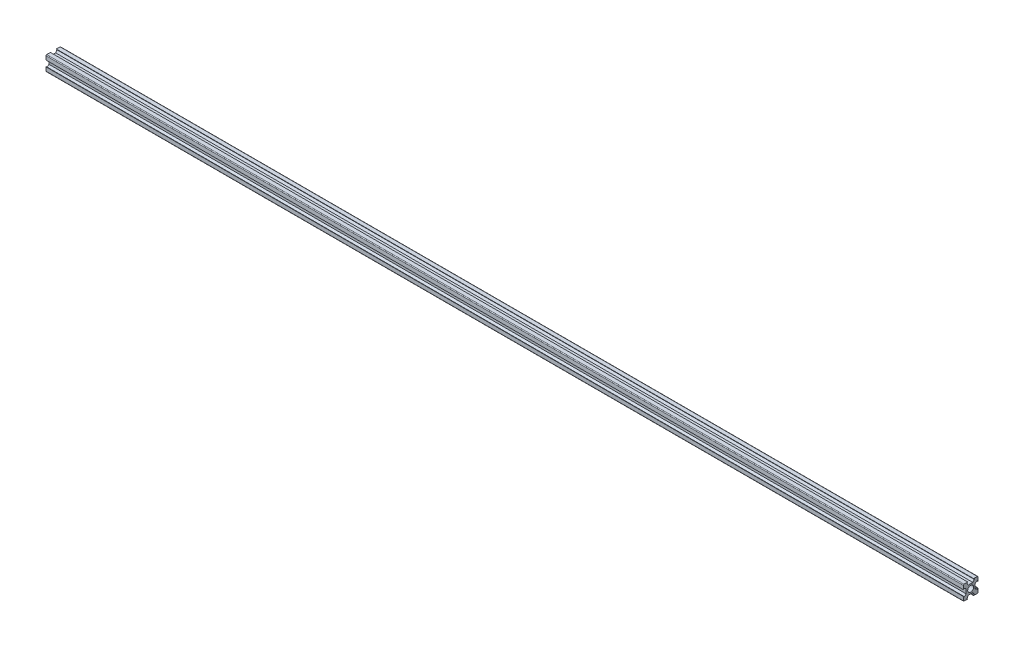
SolidWorks part; units mm, degrees
ref_plane "前视基准面" through (0, 0, 0) normal (0, 0, 1) x (1, 0, 0)
ref_plane "上视基准面" through (0, 0, 0) normal (0, 1, 0) x (1, 0, 0)
ref_plane "右视基准面" through (0, 0, 0) normal (1, 0, 0) x (0, 0, -1)
sketch "草图1" plane through (0, 0, 0) normal (0, 0, 1) x (1, 0, 0)
  line L1 (-66.5187, -1.3979) -> (1179.4813, -1.3979)
  line L2 (-66.5187, -1.3979) -> (-66.5187, -11.3979)
  line L3 (-66.5187, -11.3979) -> (1179.4813, -11.3979)
  line L4 (1179.4813, -1.3979) -> (1179.4813, -11.3979)
  dimension "D1" = 10
  dimension "D2" = 1246
extrude "凸台-拉伸1" add sketch "草图1" along normal blind 10
sketch "草图2" plane through (1179.4813, 0, 0) normal (1, 0, 0) x (0, 0, -1)
  circle A0 centre (0, -11.3979) radius 4
  dimension "D1" = 8
extrude "切除-拉伸1" cut sketch "草图2" against normal blind 1270
sketch "草图3" plane through (1179.4813, 0, 0) normal (1, 0, 0) x (0, 0, -1)
  line L0 (-4, -1.3979) -> (0, -1.3979)
  line L1 (-10, -11.3979) -> (-10, -1.3979) construction
  line L2 (-10, -1.3979) -> (0, -1.3979) construction
  line L3 (-10, -7.3979) -> (-10, -11.3979)
  line L4 (-4, -1.3979) -> (-4, -1.8979)
  line L5 (-4, -1.8979) -> (-5.5, -1.8979)
  line L6 (-3, -5.3979) -> (0, -5.3979)
  line L7 (0, -7.3979) -> (0, -1.3979) construction
  line L8 (0, -5.3979) -> (0, -1.3979)
  line L9 (-10, -11.3979) -> (-6, -11.3979)
  line L10 (-10, -11.3979) -> (-4, -11.3979) construction
  line L11 (-6, -11.3979) -> (-6, -8.3979)
  line L12 (-10, -7.3979) -> (-9.5, -7.3979)
  line L13 (-9.5, -7.3979) -> (-9.5, -5.8979)
  line L14 (-5.5, -1.8979) -> (-3, -5.3979)
  line L15 (-9.5, -5.8979) -> (-6, -8.3979)
  dimension "D1" = 4
  dimension "D2" = 4
  dimension "D3" = 4
  dimension "D4" = 4
  dimension "D5" = 0.5
  dimension "D6" = 0.5
  dimension "D7" = 3
  dimension "D8" = 3
  dimension "D9" = 1.5
  dimension "D10" = 1.5
extrude "切除-拉伸2" cut sketch "草图3" against normal blind 1270
fillet "圆角1" radius 1 1 edges at (556.4813, -1.3979, 10)
pattern_circular "阵列(圆周)2" count 4 every 90 about axis through (0, -11.3979, 0) along (1, 0, 0) of "凸台-拉伸1", "圆角1", "切除-拉伸1", "切除-拉伸2"
